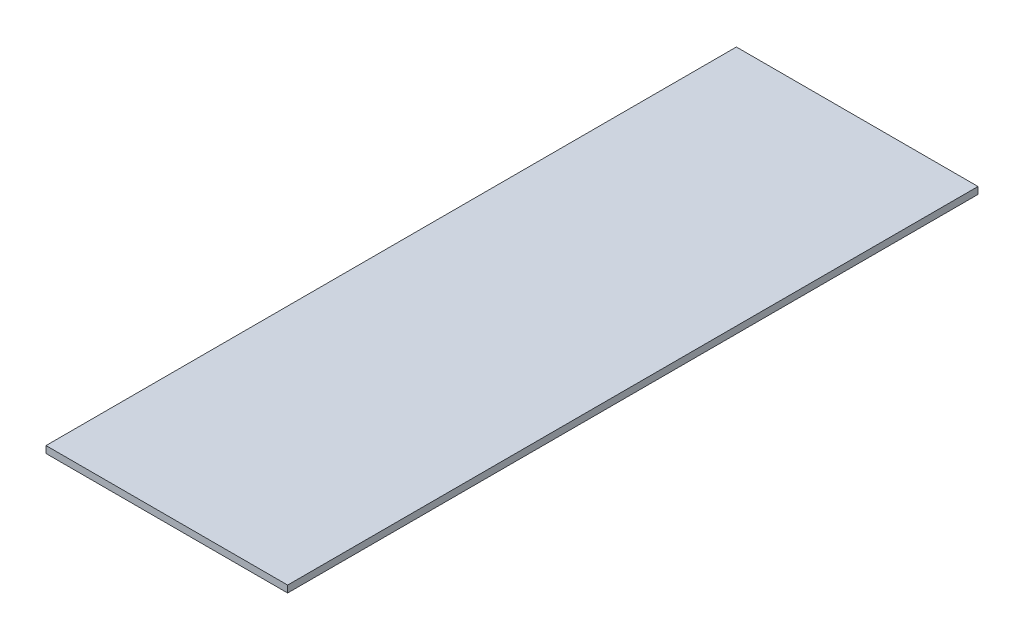
SolidWorks part; units mm, degrees
material "Aleación 1060"
ref_plane "Alzado" through (0, 0, 0) normal (0, 0, 1) x (1, 0, 0)
ref_plane "Planta" through (0, 0, 0) normal (0, 1, 0) x (1, 0, 0)
ref_plane "Vista lateral" through (0, 0, 0) normal (1, 0, 0) x (0, 0, -1)
sketch "Croquis1" plane through (0, 0, 0) normal (0, 1, 0) x (1, 0, 0)
  line L1 (-193.2886, 91.9463) -> (-123.2886, 91.9463)
  line L2 (-193.2886, 91.9463) -> (-193.2886, -108.0537)
  line L3 (-193.2886, -108.0537) -> (-123.2886, -108.0537)
  line L4 (-123.2886, 91.9463) -> (-123.2886, -108.0537)
  dimension "D1" = 200
  dimension "D2" = 70
extrude "Saliente-Extruir1" add sketch "Croquis1" along normal blind 2
